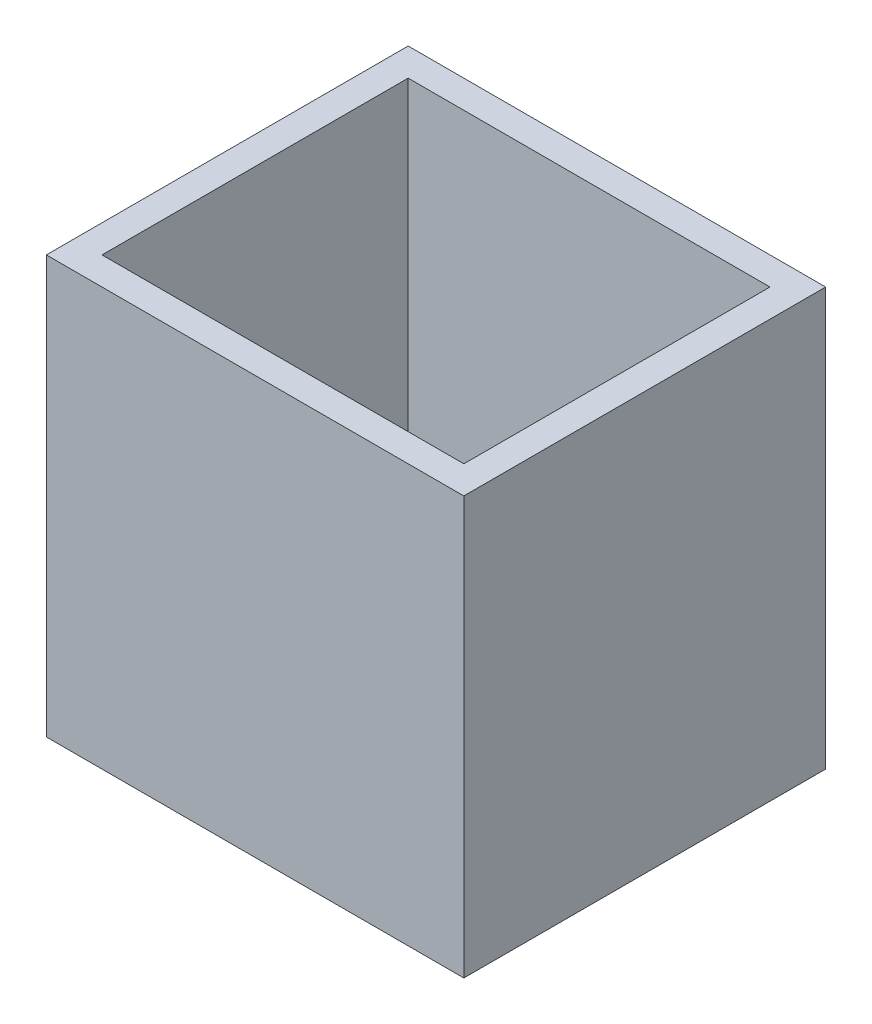
SolidWorks part; units mm, degrees
ref_plane "Front Plane" through (0, 0, 0) normal (0, 0, 1) x (1, 0, 0)
ref_plane "Top Plane" through (0, 0, 0) normal (0, 1, 0) x (1, 0, 0)
ref_plane "Right Plane" through (0, 0, 0) normal (1, 0, 0) x (0, 0, -1)
sketch "Sketch1" plane through (0, 0, 0) normal (0, 0, 1) x (1, 0, 0)
  line L1 (0, 0) -> (150, 0)
  line L2 (0, 0) -> (0, 150)
  line L3 (0, 150) -> (150, 150)
  line L4 (150, 0) -> (150, 150)
  dimension "D1" = 150
  dimension "D2" = 150
extrude "Boss-Extrude2" add sketch "Sketch1" along normal blind 130
sketch "Sketch3" plane through (0, 150, 0) normal (0, 1, 0) x (1, 0, 0)
  line L8 (140, -10) -> (10, -10)
  line L9 (10, -10) -> (10, -120)
  line L10 (10, -120) -> (140, -120)
  line L11 (140, -120) -> (140, -10)
  line L12 (140, -10) -> (10, -10)
  line L13 (10, -10) -> (10, -120)
  line L14 (10, -120) -> (140, -120)
  line L15 (140, -120) -> (140, -10)
  dimension "D1" = 10
extrude "Cut-Extrude2" cut sketch "Sketch3" against normal blind 110
